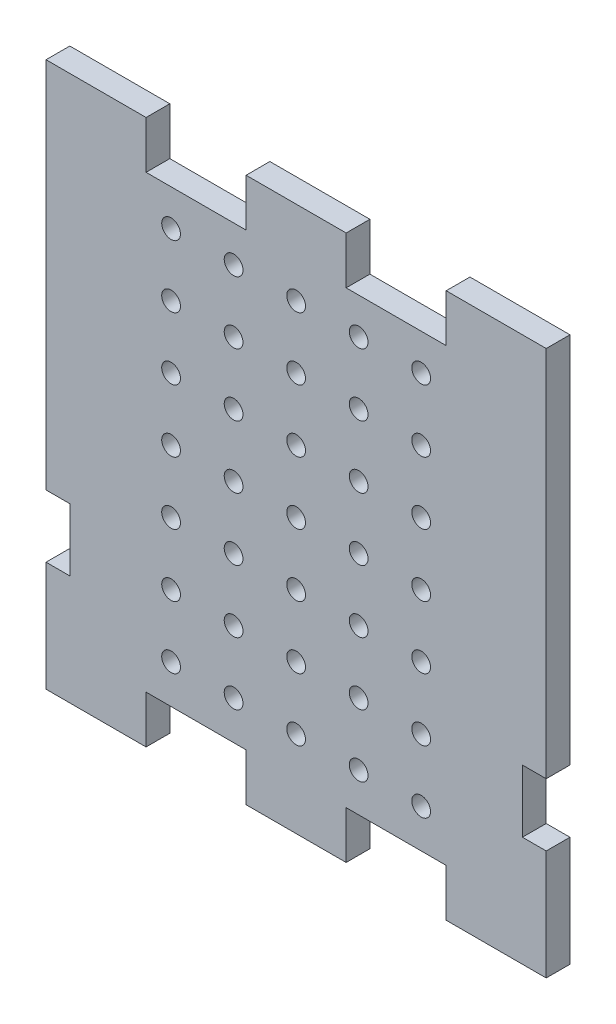
SolidWorks part; units mm, degrees
ref_plane "Front Plane" through (0, 0, 0) normal (0, 0, 1) x (1, 0, 0)
ref_plane "Top Plane" through (0, 0, 0) normal (0, 1, 0) x (1, 0, 0)
ref_plane "Right Plane" through (0, 0, 0) normal (1, 0, 0) x (0, 0, -1)
sketch "Sketch1" plane through (0, 0, 0) normal (0, 0, 1) x (1, 0, 0)
  line L0 (0, 9.652) -> (20.32, 9.652) construction
  line L1 (0, 0) -> (101.6, 0)
  line L2 (0, 0) -> (0, 110.744)
  line L3 (0, 110.744) -> (101.6, 110.744)
  line L4 (101.6, 0) -> (101.6, 110.744)
  line L5 (20.32, 0) -> (40.64, 0)
  line L6 (20.32, 0) -> (20.32, 9.652)
  line L7 (20.32, 9.652) -> (40.64, 9.652)
  line L8 (40.64, 0) -> (40.64, 9.652)
  line L9 (60.96, 0) -> (81.28, 0)
  line L10 (60.96, 0) -> (60.96, 9.652)
  line L11 (60.96, 9.652) -> (81.28, 9.652)
  line L12 (81.28, 0) -> (81.28, 9.652)
  line L13 (40.64, 9.652) -> (60.96, 9.652) construction
  line L14 (101.6, 9.652) -> (81.28, 9.652) construction
  line L15 (0, 55.372) -> (101.6, 55.372) construction
  line L16 (101.6, 101.092) -> (81.28, 101.092) construction
  line L17 (40.64, 101.092) -> (60.96, 101.092) construction
  line L18 (0, 101.092) -> (20.32, 101.092) construction
  line L19 (81.28, 110.744) -> (81.28, 101.092)
  line L20 (60.96, 101.092) -> (81.28, 101.092)
  line L21 (60.96, 110.744) -> (60.96, 101.092)
  line L22 (60.96, 110.744) -> (81.28, 110.744)
  line L23 (40.64, 110.744) -> (40.64, 101.092)
  line L24 (20.32, 101.092) -> (40.64, 101.092)
  line L25 (20.32, 110.744) -> (20.32, 101.092)
  line L26 (20.32, 110.744) -> (40.64, 110.744)
  line L27 (0, 110.744) -> (101.6, 110.744)
  line L28 (101.6, 9.652) -> (81.28, 9.652) construction
  dimension "D1" = 110.744
  dimension "D2" = 101.6
  dimension "D3" = 9.652
extrude "Boss-Extrude1" add sketch "Sketch1" along normal blind 4.826 contours L25 L3 L2 L1 L6 L7 L8 L10 L11 L12 L4 L19 L20 L21 L23 L24
sketch "Sketch2" plane through (0, 0, 4.826) normal (0, 0, 1) x (1, 0, 0)
  circle A0 centre (50.8, 68.326) radius 1.905
  circle A1 centre (63.5, 68.326) radius 1.905
  circle A2 centre (76.2, 68.326) radius 1.905
  circle A3 centre (63.5, 81.026) radius 1.905
  circle A4 centre (76.2, 81.026) radius 1.905
  circle A5 centre (63.5, 93.726) radius 1.905
  circle A6 centre (76.2, 93.726) radius 1.905
  circle A11 centre (38.1, 68.326) radius 1.905
  circle A12 centre (25.4, 68.326) radius 1.905
  circle A13 centre (38.1, 81.026) radius 1.905
  circle A14 centre (25.4, 81.026) radius 1.905
  circle A15 centre (50.8, 106.426) radius 1.905 [skipped]
  circle A16 centre (50.8, 93.726) radius 1.905 [skipped]
  circle A17 centre (50.8, 81.026) radius 1.905 [skipped]
  circle A18 centre (50.8, 119.126) radius 1.905 [skipped]
  circle A19 centre (38.1, 93.726) radius 1.905
  circle A20 centre (25.4, 93.726) radius 1.905
  circle A25 centre (50.8, 81.026) radius 1.905
  circle A26 centre (50.8, 93.726) radius 1.905
  circle A29 centre (63.5, 68.326) radius 1.905 [skipped]
  circle A30 centre (76.2, 68.326) radius 1.905 [skipped]
  circle A31 centre (63.5, 55.626) radius 1.905
  circle A32 centre (76.2, 55.626) radius 1.905
  circle A33 centre (63.5, 42.926) radius 1.905
  circle A34 centre (76.2, 42.926) radius 1.905
  circle A35 centre (63.5, 30.226) radius 1.905
  circle A36 centre (76.2, 30.226) radius 1.905
  circle A37 centre (63.5, 17.526) radius 1.905
  circle A38 centre (76.2, 17.526) radius 1.905
  circle A39 centre (38.1, 55.626) radius 1.905
  circle A40 centre (25.4, 55.626) radius 1.905
  circle A41 centre (38.1, 42.926) radius 1.905
  circle A42 centre (25.4, 42.926) radius 1.905
  circle A43 centre (25.4, 68.326) radius 1.905 [skipped]
  circle A44 centre (38.1, 68.326) radius 1.905 [skipped]
  circle A45 centre (50.8, 55.626) radius 1.905 [skipped]
  circle A46 centre (50.8, 42.926) radius 1.905 [skipped]
  circle A47 centre (50.8, 30.226) radius 1.905 [skipped]
  circle A48 centre (50.8, 17.526) radius 1.905 [skipped]
  circle A49 centre (38.1, 30.226) radius 1.905
  circle A50 centre (25.4, 30.226) radius 1.905
  circle A51 centre (38.1, 17.526) radius 1.905
  circle A52 centre (25.4, 17.526) radius 1.905
  circle A53 centre (50.8, 55.626) radius 1.905
  circle A54 centre (50.8, 42.926) radius 1.905
  circle A55 centre (50.8, 30.226) radius 1.905
  circle A56 centre (50.8, 17.526) radius 1.905
  circle A57 centre (63.5, 106.426) radius 1.905 [skipped]
  circle A58 centre (76.2, 106.426) radius 1.905 [skipped]
  circle A59 centre (63.5, 119.126) radius 1.905 [skipped]
  circle A60 centre (76.2, 119.126) radius 1.905 [skipped]
  circle A61 centre (38.1, 106.426) radius 1.905 [skipped]
  circle A62 centre (25.4, 106.426) radius 1.905 [skipped]
  circle A63 centre (38.1, 119.126) radius 1.905 [skipped]
  circle A64 centre (25.4, 119.126) radius 1.905 [skipped]
  circle A65 centre (50.8, 106.426) radius 1.905 [skipped]
  circle A66 centre (50.8, 119.126) radius 1.905 [skipped]
  dimension "D1" = 3.81
  dimension "D2" = 3
  dimension "D3" = 5
  dimension "D4" = 3
  dimension "D5" = 5
  dimension "D6" = 3
  dimension "D7" = 5
  dimension "D8" = 3
  dimension "D9" = 5
extrude "Cut-Extrude1" cut sketch "Sketch2" against normal through all
sketch "Sketch3" plane through (0, 0, 4.826) normal (0, 0, 1) x (1, 0, 0)
  line L0 (0, 35.052) -> (4.826, 35.052) construction
  line L1 (4.826, 35.052) -> (4.826, 22.352) construction
  line L2 (0, 22.352) -> (4.826, 22.352) construction
  line L3 (0, 35.052) -> (0, 22.352) construction
  line L4 (96.774, 35.052) -> (96.774, 22.352) construction
  line L5 (101.6, 35.052) -> (96.774, 35.052) construction
  line L6 (101.6, 35.052) -> (101.6, 22.352) construction
  line L7 (101.6, 22.352) -> (96.774, 22.352) construction
  line L8 (0, 35.052) -> (4.826, 35.052)
  line L9 (4.826, 35.052) -> (4.826, 22.352)
  line L10 (0, 22.352) -> (4.826, 22.352)
  line L11 (0, 35.052) -> (0, 22.352)
  line L12 (96.774, 35.052) -> (96.774, 22.352)
  line L13 (101.6, 35.052) -> (96.774, 35.052)
  line L14 (101.6, 35.052) -> (101.6, 22.352)
  line L15 (101.6, 22.352) -> (96.774, 22.352)
extrude "Cut-Extrude2" cut sketch "Sketch3" against normal through all
equation "\"MDF\"= 0.19in"
equation "\"PVCID\" = 2.067in"
equation "\"PVCOD\" = 2.375in"
equation "\"GenDiameter\"= 60mm"
equation "\"GenCutDiameter\" = 1.8in"
equation "\"GenCutDistance\" = 1"
equation "\"TowerHeight\" = 6in"
equation "\"TowerFrontBase\" = 3in"
equation "\"FunnelHeight\" = 1in"
equation "\"FunnelAngle\" = 20"
equation "\"TowerSideBase\" = 3in"
equation "\"TowerPanelLength\" = 2in"
equation "\"TowerPanelLeeway\" = 0.5in"
equation "\"BaseLength\" = 9in"
equation "\"BaseWidth\" = 10in"
equation "\"WheelHoleLength\" = 3.25in"
equation "\"WheelHoleWidth\" = 26mm"
equation "\"WheelHoleFromBack\" = 1.5in"
equation "\"DropLength\" = 1in"
equation "\"DropWidth\" = 8.5in"
equation "\"BumperWidth\" = 2in"
equation "\"SmallHexDiameter\" = 0.185in"
equation "\"SmallHexHeight\" = 0.701in"
equation "\"ScrewSize\" = 0.106in"
equation "\"BigHexDiameter\" = 0.251in"
equation "\"BigHexHeight\" = 0.374in"
equation "\"PCBThickness\" = 0.066in"
equation "\"ConnectorHeight\" = 0.517in"
equation "\"BoardHeight\" = 0.583in"
equation "\"UnoStackHeight\" = 1.351in"
equation "\"UnoStackWidth\" = 3.053in"
equation "\"UnoStackLength\" = 3.152in"
equation "\"HBridgeWidth\" = 1.797in"
equation "\"HBridgeLength\" = 2.236in"
equation "\"DSWidth\" = 1.820in"
equation "\"DSLength\" = 1.833in"
equation "\"StepperWidth\" = 1.799in"
equation "\"StepperLength\" = 2.248in"
equation "\"ULNWidth\" = 1.304in"
equation "\"ULNLength\" = 1.545in"
equation "\"VSwitchHeight\" = 0.392in"
equation "\"VSwitchWidth\" = 0.637in"
equation "\"VSwitchLength\" = 1.097in"
equation "\"SkateWheelDiameter\" = 80mm"
equation "\"SkateWheelThickness\" = 24mm"
equation "\"BaseDistance\" = 3in"
equation "\"DummyVar\" = 2in"
equation "\"D1@Sketch1\"=\"MDF\"*4+3.6in"
equation "\"D1@Boss-Extrude1\"=\"MDF\""
equation "\"D3@Sketch1\"=\"MDF\"*2"
